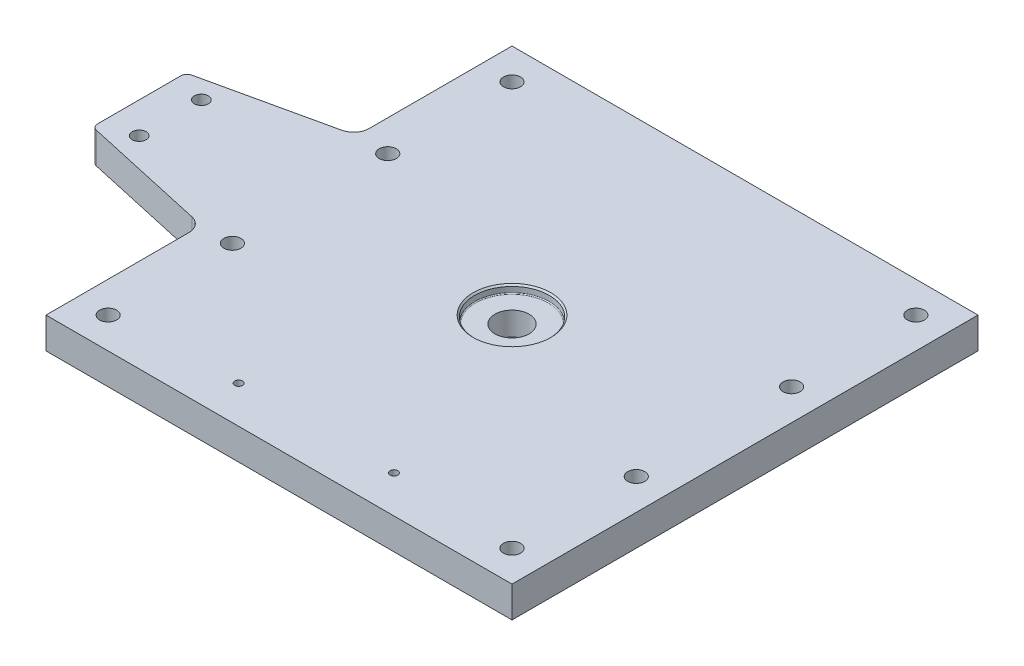
SolidWorks part; units mm, degrees
material "ALUMINIUM,  6082-T6"
ref_plane "Front Plane" through (0, 0, 0) normal (0, 0, 1) x (1, 0, 0)
ref_plane "Top Plane" through (0, 0, 0) normal (0, 1, 0) x (1, 0, 0)
ref_plane "Right Plane" through (0, 0, 0) normal (1, 0, 0) x (0, 0, -1)
sketch "Sketch1" plane through (0, 0, 0) normal (0, 1, 0) x (1, 0, 0)
  line L0 (-75, 75) -> (75, -75) construction
  line L1 (75, 75) -> (-75, 75)
  line L2 (75, 75) -> (75, -75)
  line L3 (75, -75) -> (-75, -75)
  line L4 (-75, 75) -> (-75, -75)
  dimension "D1" = 150
extrude "Boss-Extrude1" add sketch "Sketch1" along normal mid plane 10
hole_wizard "CBORE for M5 Hex Socket Head Cap Screw1" positions "Sketch2" profile "Sketch3" counterbore size "M5" standard "ISO" end condition through all
sketch "Sketch2" plane through (0, -5, 0) normal (0, -1, 0) x (-1, 0, 0)
  line L0 (-65, -65) -> (-65, -25) construction
  line L1 (-65, -25) -> (-65, 25) construction
  line L2 (-65, 25) -> (-65, 65) construction
  line L3 (65, -65) -> (65, -25) construction
  line L4 (65, -25) -> (65, 25) construction
  line L5 (65, 25) -> (65, 65) construction
  line L7 (-65, 65) -> (65, 65) construction
  line L10 (65, -65) -> (-65, -65) construction
  line L13 (-65, -25) -> (65, -25) construction
  line L16 (65, 25) -> (-65, 25) construction
  line L17 (-65, 25) -> (65, -25) construction
  line L18 (75, -75) -> (-75, -75) construction
  line L20 (-75, -75) -> (-75, 75) construction
  point P3 (-65, -65)
  point P4 (-65, -25)
  point P5 (-65, 25)
  point P6 (-65, 65)
  point P13 (65, -65)
  point P14 (65, -25)
  point P15 (65, 25)
  point P16 (65, 65)
  dimension "D1" = 10
  dimension "D2" = 40
  dimension "D4" = 10
sketch "Sketch3" plane through (65, -5, 65) normal (1, 0, 0) x (0, 0, -1)
  line L0 (0, 0) -> (0, 10)
  line L1 (0, 10) -> (2.75, 10)
  line L3 (2.75, 10) -> (2.75, 5.5)
  line L4 (2.75, 5.5) -> (5, 5.5)
  line L5 (5, 5.5) -> (5, 0)
  line L7 (5, 0) -> (0, 0)
  line L11 (0, -6.35) -> (0, 107.95) construction
  dimension "Thru Hole Dia." = 5.5
  dimension "Thru Hole Depth" = 10
  dimension "C'Bore Dia." = 10
  dimension "C'Bore Depth" = 5.5
hole_wizard "Ø11.0 (11) Diameter Hole1" positions "Sketch4" profile "Sketch5" hole size "Ø11.0" standard "ISO" end condition through all
sketch "Sketch4" plane through (0, -5, 0) normal (0, -1, 0) x (-1, 0, 0)
  point P0 (0, 0)
sketch "Sketch5" plane through (0, -5, 0) normal (1, 0, 0) x (0, 0, -1)
  line L0 (0, 0) -> (0, 10)
  line L1 (0, 10) -> (5.5, 10)
  line L2 (5.5, 10) -> (5.5, 0)
  line L5 (5.5, 0) -> (0, 0)
  line L11 (0, -6.35) -> (0, 107.95) construction
  dimension "Thru Hole Dia." = 11
  dimension "Thru Hole Depth" = 10
sketch "Sketch6" plane through (0, 5, 0) normal (0, -1, 0) x (1, 0, 0)
  circle A0 centre (0, 0) radius 12
  dimension "D1" = 24
extrude "Cut-Extrude1" cut sketch "Sketch6" along normal blind 2.5
fillet "Fillet2" radius 0.3 1 edges at (0, 2.5, -12)
sketch "Sketch7" plane through (0, 5, 0) normal (0, 1, 0) x (1, 0, 0)
  line L0 (-75, 25) -> (-75, -25)
  line L1 (-75, -25) -> (-120, -15)
  line L2 (-120, -15) -> (-120, 15)
  line L3 (-120, 15) -> (-75, 25)
  line L4 (-75, 0) -> (-120, 0) construction
  line L6 (-75, 75) -> (-75, -75) construction
  dimension "D1" = 45
  dimension "D2" = 50
  dimension "D3" = 30
extrude "Boss-Extrude2" add sketch "Sketch7" against normal blind 10
fillet "Fillet3" radius 5 2 edges at (-75, 0, -25) (-75, 0, 25)
hole_wizard "Ø4.5 (4.5) Diameter Hole1" positions "Sketch9" profile "Sketch10" hole size "Ø4.5" standard "ISO" end condition through all
sketch "Sketch9" plane through (0, 5, 0) normal (0, 1, 0) x (1, 0, 0)
  line L0 (-110, 10) -> (-110, -10) construction
  line L1 (-110, 0) -> (-120, 0) construction
  line L4 (-120, 15) -> (-120, -15) construction
  point P0 (-110, 10)
  point P2 (-110, -10)
  dimension "D1" = 20
  dimension "D2" = 110
sketch "Sketch10" plane through (-110, 5, -10) normal (1, 0, 0) x (0, 0, 1)
  line L0 (0, 0) -> (0, 10)
  line L1 (0, 10) -> (2.25, 10)
  line L2 (2.25, 10) -> (2.25, 0)
  line L5 (2.25, 0) -> (0, 0)
  line L11 (0, -6.35) -> (0, 107.95) construction
  dimension "Thru Hole Dia." = 4.5
  dimension "Thru Hole Depth" = 10
fillet "Fillet4" radius 2 2 edges at (-120, 0, 15) (-120, 0, -15)
hole_wizard "M3 Tapped Hole1" positions "Sketch11" profile "Sketch12" tap size "M3" standard "ISO" end condition through all
sketch "Sketch11" plane through (0, 5, 0) normal (0, 1, 0) x (1, 0, 0)
  line L0 (-25, -63) -> (25, -63) construction
  line L2 (0, 0) -> (0, -63) construction
  line L4 (-75, -75) -> (75, -75) construction
  point P0 (-25, -63)
  point P6 (25, -63)
  dimension "D1" = 25
  dimension "D4" = 12
sketch "Sketch12" plane through (-25, 5, 63) normal (1, 0, 0) x (0, 0, 1)
  line L0 (0, 0) -> (0, 10)
  line L1 (0, 10) -> (1.25, 10)
  line L2 (1.25, 10) -> (1.25, 0)
  line L5 (1.25, 0) -> (0, 0)
  line L11 (0, -6.35) -> (0, 107.95) construction
  dimension "Thru Tap Drill Dia." = 2.5
  dimension "Thru Tap Drill Depth" = 10
cosmetic thread "Hole Thread3" parameters "D2"=3
cosmetic thread "Hole Thread6" parameters "D2"=3
chamfer "Chamfer1" distance 0.5 angle 45 1 edges at (0, 5, -12)
